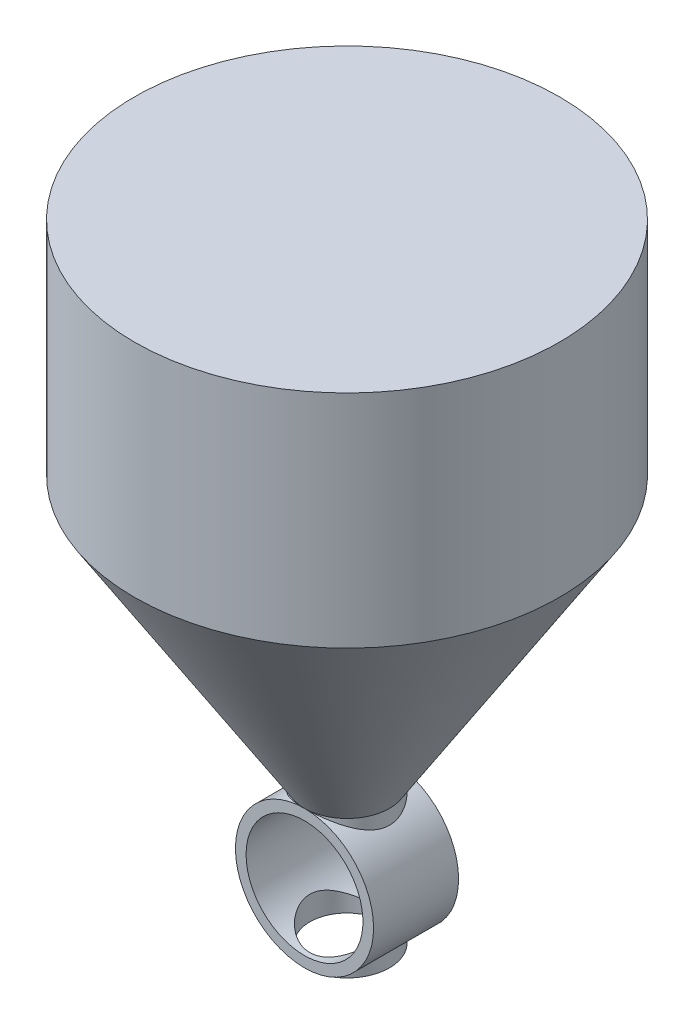
SolidWorks part; units mm, degrees
ref_plane "Alzado" through (0, 0, 0) normal (0, 0, 1) x (1, 0, 0)
ref_plane "Planta" through (0, 0, 0) normal (0, 1, 0) x (1, 0, 0)
ref_plane "Vista lateral" through (0, 0, 0) normal (1, 0, 0) x (0, 0, -1)
sketch "Croquis1" plane through (0, 0, 0) normal (0, 1, 0) x (1, 0, 0)
  circle A0 centre (0, 0) radius 100
  dimension "D1" = 200
ref_plane "Plano1" through (0, -230, 0) normal (0, 1, 0) x (1, 0, 0)
extrude "Saliente-Extruir1" add sketch "Croquis1" against normal blind 104 contours A0
sketch "Croquis2" plane through (0, -104, 0) normal (0, -1, 0) x (1, 0, 0)
  circle A2 centre (0, 0) radius 100
sketch "Croquis3" plane through (0, -230, 0) normal (0, 1, 0) x (1, 0, 0)
  circle A0 centre (0, 0) radius 20
  dimension "D1" = 40
loft "Recubrir1" add profiles "Croquis3", "Croquis2"
sketch "Croquis4" plane through (0, -230, 0) normal (0, -1, 0) x (1, 0, 0)
  circle A0 centre (0, 0) radius 20
  dimension "D1" = 40
extrude "Saliente-Extruir2" add sketch "Croquis4" along normal blind 65
ref_plane "Plano2" through (0, 0, -20) normal (0, 0, -1) x (-1, 0, 0)
sketch "Croquis5" plane through (0, 0, -20) normal (0, 0, -1) x (-1, 0, 0)
  line L0 (0, -230) -> (0, -295) construction
  line L1 (110, -230) -> (-110, -230) construction
  line L2 (-32.5, -262.5) -> (32.5, -262.5) construction
  circle A0 centre (0, -262.5) radius 32.5
  point P7 (0, -262.5)
  point P8 (0, -262.5)
  dimension "D1" = 65
  dimension "D2" = 65
extrude "Saliente-Extruir3" add sketch "Croquis5" against normal blind 40
sketch "Croquis6" plane through (0, 0, -20) normal (0, 0, -1) x (-1, 0, 0)
  circle A0 centre (0, -262.5) radius 27.5
  dimension "D1" = 55
extrude "Cortar-Extruir1" cut sketch "Croquis6" against normal through all
sketch "Croquis7" plane through (0, -295, 0) normal (0, -1, 0) x (1, 0, 0)
  circle A0 centre (0, 0) radius 17.5
  dimension "D1" = 35
extrude "Cortar-Extruir2" cut sketch "Croquis7" against normal blind 24
